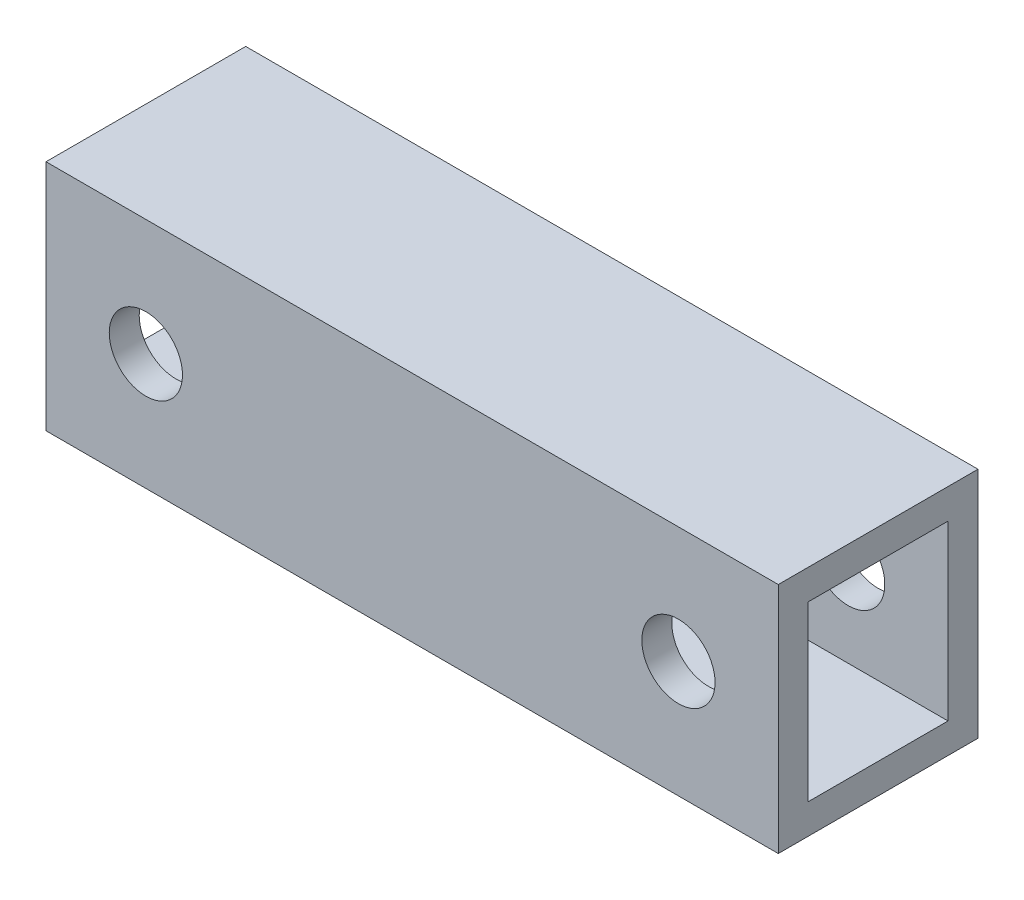
SolidWorks part; units mm, degrees
ref_plane "Front Plane" through (0, 0, 0) normal (0, 0, 1) x (1, 0, 0)
ref_plane "Top Plane" through (0, 0, 0) normal (0, 1, 0) x (1, 0, 0)
ref_plane "Right Plane" through (0, 0, 0) normal (1, 0, 0) x (0, 0, -1)
sketch "Soft_contact_and_wrap_profile" plane through (0, 0, 0) normal (0, 0, 1) x (1, 0, 0)
  line L1 (54, -17) -> (76, -17)
  line L2 (54, -17) -> (54, -10)
  line L3 (54, -10) -> (76, -10)
  line L4 (76, -17) -> (76, -10)
  dimension "D1" = 22
  dimension "D2" = 7
  dimension "D3" = 54
  dimension "D4" = 10
extrude "Soft_contact_and_wrap" add sketch "Soft_contact_and_wrap_profile" along normal blind 6 from offset 1
sketch "Fixed_bar_slip_pocket_profile" plane through (0, 0, 0) normal (0, 0, 1) x (1, 0, 0)
  line L1 (53, -16.1) -> (77, -16.1)
  line L2 (53, -16.1) -> (53, -10.9)
  line L3 (53, -10.9) -> (77, -10.9)
  line L4 (77, -16.1) -> (77, -10.9)
  dimension "D1" = 24
  dimension "D2" = 5.2
  dimension "D3" = 53
  dimension "D4" = 10.9
extrude "Slip_pocket" cut sketch "Fixed_bar_slip_pocket_profile" along normal blind 4.2 from offset 0.1
sketch "Pad_capture_M2_profile" plane through (0, 0, 0) normal (0, 0, 1) x (1, 0, 0)
  circle A0 centre (57, -13.5) radius 1.1
  circle A1 centre (73, -13.5) radius 1.1
  dimension "D1" = 2.2
  dimension "D2" = 2.2
  dimension "D3" = 57
  dimension "D4" = 73
  dimension "D5" = 13.5
extrude "Pad_capture_M2" cut sketch "Pad_capture_M2_profile" along normal through all from offset 50
